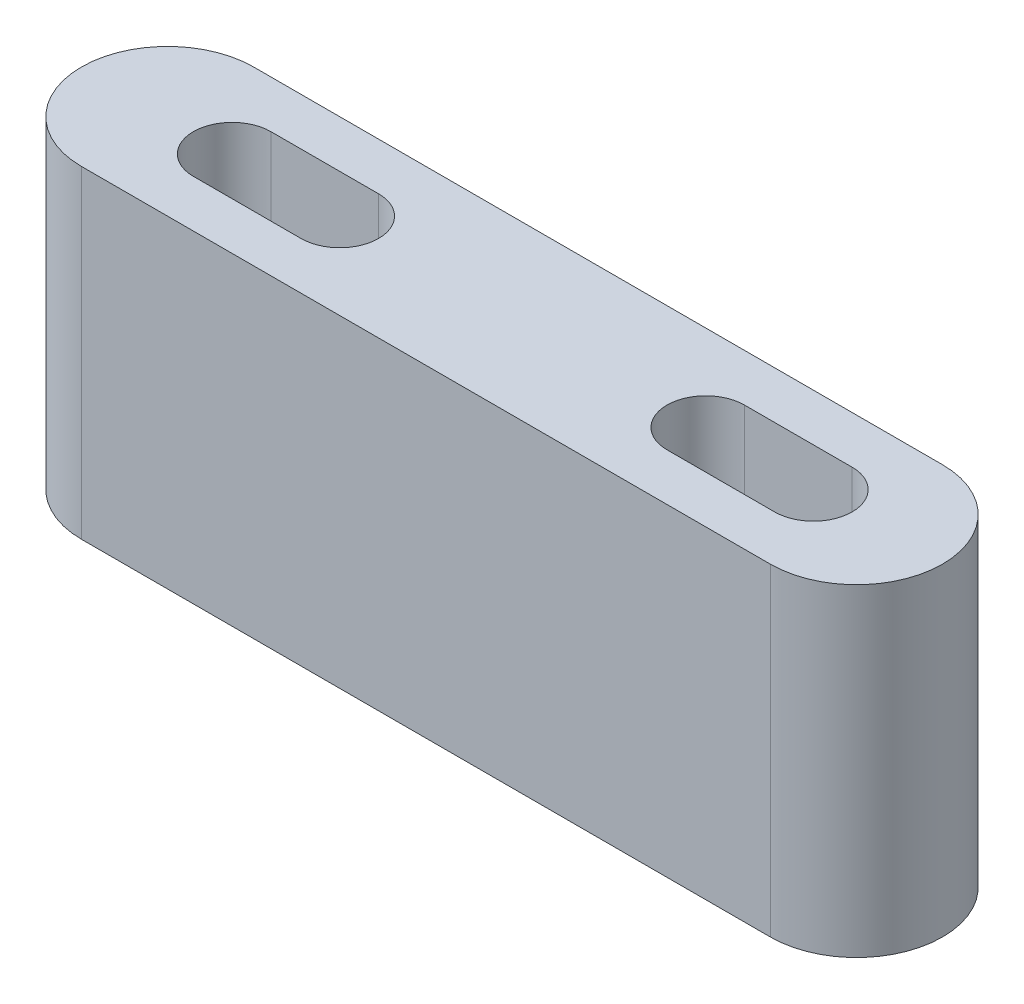
SolidWorks part; units mm, degrees
ref_plane "Front Plane" through (0, 0, 0) normal (0, 0, 1) x (1, 0, 0)
ref_plane "Top Plane" through (0, 0, 0) normal (0, 1, 0) x (1, 0, 0)
ref_plane "Right Plane" through (0, 0, 0) normal (1, 0, 0) x (0, 0, -1)
sketch "Sketch5" plane through (0, 0, 0) normal (0, 1, 0) x (1, 0, 0)
  line L0 (0, 0) -> (32, 0)
  line L3 (0, 8) -> (32, 8)
  arc A0 (0, 8) -> (0, 0) centre (0, 4) ccw
  arc A1 (32, 0) -> (32, 8) centre (32, 4) ccw
  dimension "D1" = 8
  dimension "D2" = 32
extrude "Boss-Extrude2" add sketch "Sketch5" along normal blind 15
sketch "Sketch8" plane through (0, 15, 0) normal (0, 1, 0) x (1, 0, 0)
  line L0 (3, 4) -> (8, 4) construction
  line L1 (3, 5.8) -> (8, 5.8)
  line L2 (3, 2.2) -> (8, 2.2)
  line L3 (25, 4) -> (30, 4) construction
  line L4 (25, 5.8) -> (30, 5.8)
  line L5 (25, 2.2) -> (30, 2.2)
  line L6 (-1004, 4) -> (48996, 4) construction
  arc A0 (3, 5.8) -> (3, 2.2) centre (3, 4) ccw
  arc A1 (8, 2.2) -> (8, 5.8) centre (8, 4) ccw
  arc A2 (25, 5.8) -> (25, 2.2) centre (25, 4) ccw
  arc A3 (30, 2.2) -> (30, 5.8) centre (30, 4) ccw
  arc A4 (0, 8) -> (0, 0) centre (0, 4) ccw construction
  point P2 (5.5, 4)
  point P7 (27.5, 4)
  point P20 (-4, 4)
  dimension "D2" = 1.8
  dimension "D1" = 5
  dimension "D3" = 22
  dimension "D4" = 5.5
extrude "Cut-Extrude1" cut sketch "Sketch8" against normal through all
sketch "Sketch1" plane through (0, 0, 0) normal (0, 1, 0) x (1, 0, 0)
  line L1 (0, 0) -> (16, 0)
  line L3 (0, 8) -> (16, 8)
  arc A0 (0, 8) -> (0, 0) centre (0, 4) ccw
  arc A1 (16, 0) -> (16, 8) centre (16, 4) ccw
  dimension "D1" = 8
  dimension "D2" = 16
extrude "Boss-Extrude1" [suppressed] add sketch "Sketch1" along normal blind 15
hole_wizard "M3 Clearance Hole1" [suppressed] positions "Sketch3" profile "Sketch4" hole size "M3" standard "ANSI Metric"
sketch "Sketch3" [suppressed] plane through (0, 15, 0) normal (0, 1, 0) x (1, 0, 0)
  line L0 (-1000, 4) -> (49000, 4) construction
  line L2 (8, 8) -> (8, 0) construction
  line L3 (16, 8) -> (0, 8) construction
  line L4 (0, 0) -> (16, 0) construction
  arc A0 (0, 8) -> (0, 0) centre (0, 4) ccw construction
  point P0 (2, 4)
  point P2 (14, 4)
  point P27 (-4, 4)
  dimension "D1" = 6
sketch "Sketch4" plane through (2, 15, -4) normal (1, 0, 0) x (0, 0, 1)
  line L0 (0, 0) -> (0, 15)
  line L1 (0, 15) -> (1.8, 15)
  line L2 (1.8, 15) -> (1.8, 0)
  line L5 (1.8, 0) -> (0, 0)
  line L11 (0, -6.35) -> (0, 107.95) construction
  dimension "Thru Hole Dia." = 3.6
  dimension "Thru Hole Depth" = 15
equation "\"D2@Sketch8\"=3.6/2"
